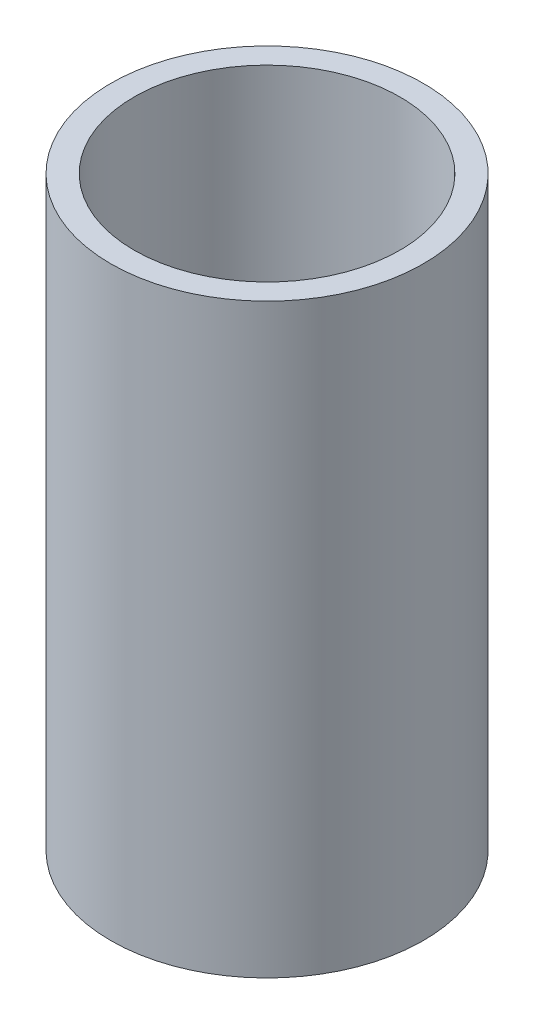
SolidWorks part; units mm, degrees
ref_plane "前视基准面" through (0, 0, 0) normal (0, 0, 1) x (1, 0, 0)
ref_plane "上视基准面" through (0, 0, 0) normal (0, 1, 0) x (1, 0, 0)
ref_plane "右视基准面" through (0, 0, 0) normal (1, 0, 0) x (0, 0, -1)
other "Configuration Table"
sketch "草图1" plane through (0, 0, 0) normal (0, 1, 0) x (1, 0, 0)
  circle A14 centre (0, 0) radius 16
  circle A15 centre (0, 0) radius 13.6
  dimension "D1" = 32
  dimension "D2" = 2.4
extrude "凸台-拉伸1" add sketch "草图1" along normal blind 60
